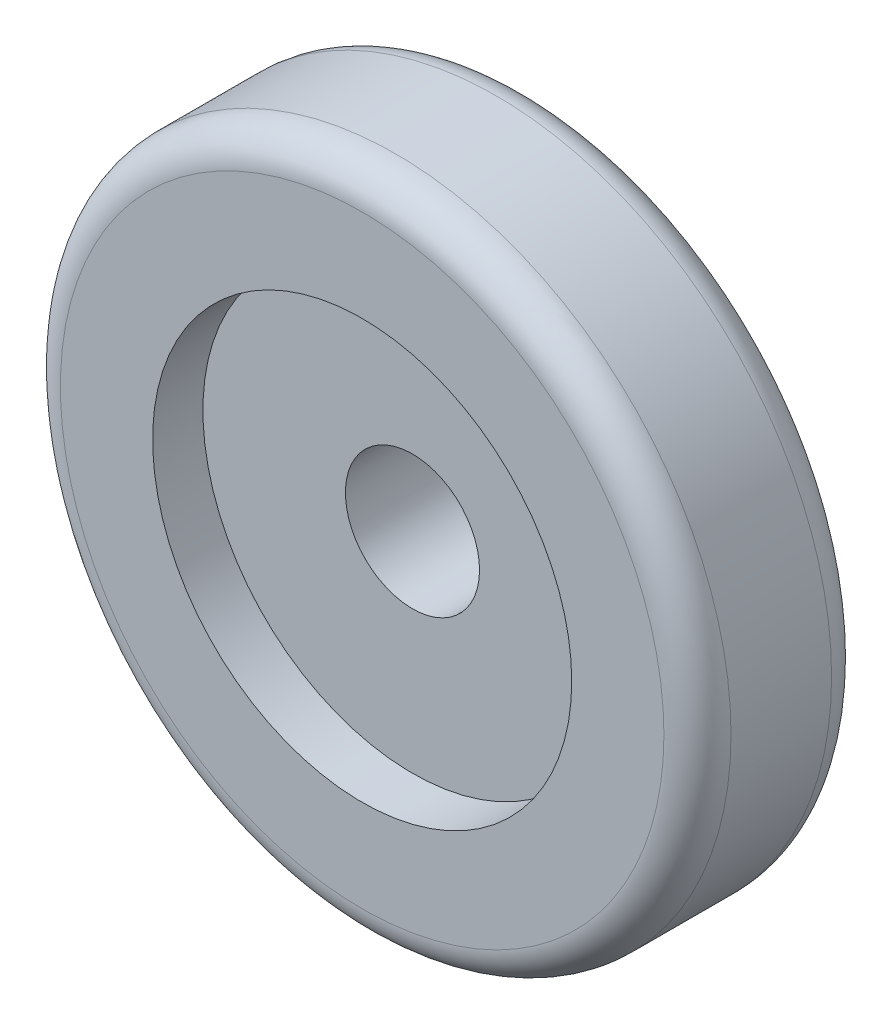
SolidWorks part; units mm, degrees
ref_plane "Front Plane" through (0, 0, 0) normal (0, 0, 1) x (1, 0, 0)
ref_plane "Top Plane" through (0, 0, 0) normal (0, 1, 0) x (1, 0, 0)
ref_plane "Right Plane" through (0, 0, 0) normal (1, 0, 0) x (0, 0, -1)
sketch "Sketch1" plane through (0, 0, 0) normal (0, 0, 1) x (1, 0, 0)
  circle A0 centre (0, 0) radius 4
  circle A1 centre (0, 0) radius 20
  dimension "D1" = 40
  dimension "D2" = 8
extrude "Boss-Extrude1" add sketch "Sketch1" along normal blind 10
sketch "Sketch2" plane through (0, 0, 10) normal (0, 0, 1) x (1, 0, 0)
  circle A0 centre (0, 0) radius 12.5
  dimension "D1" = 25
extrude "Cut-Extrude1" cut sketch "Sketch2" against normal blind 3
fillet "Fillet1" radius 2 2 edges at (20, 0, 0) (20, 0, 10)
